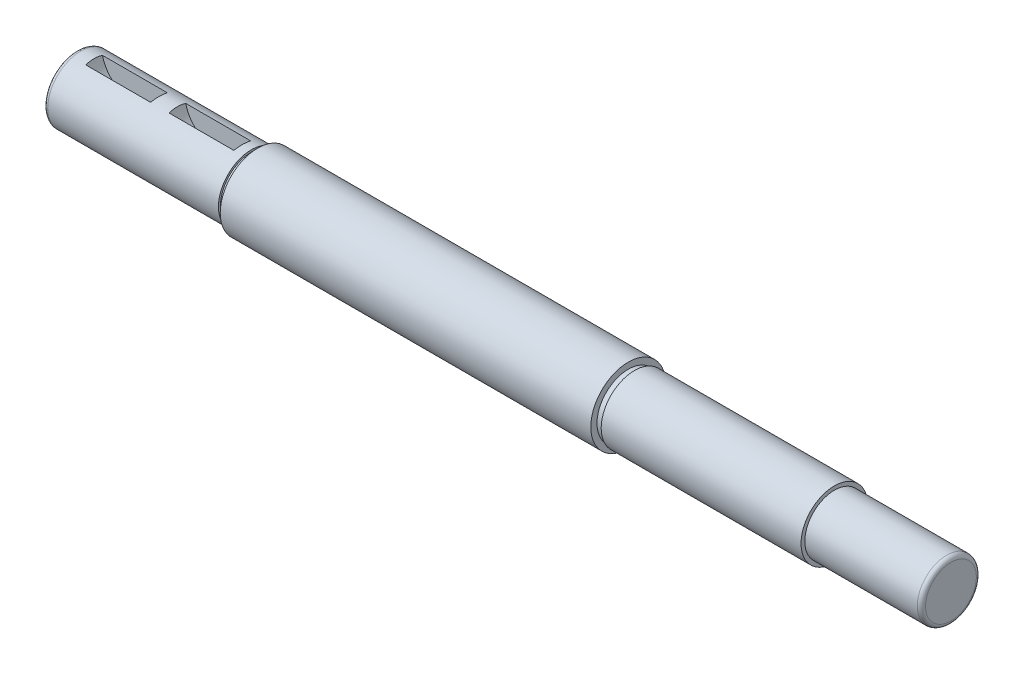
SolidWorks part; units mm, degrees
material "A-1"
ref_plane "Front Plane" through (0, 0, 0) normal (0, 0, 1) x (1, 0, 0)
ref_plane "Top Plane" through (0, 0, 0) normal (0, 1, 0) x (1, 0, 0)
ref_plane "Right Plane" through (0, 0, 0) normal (1, 0, 0) x (0, 0, -1)
sketch "Sketch1" plane through (0, 0, 0) normal (0, 0, 1) x (1, 0, 0)
  line L0 (-43.2189, 0) -> (45516.3918, 0) construction
  line L2 (-54.6287, 0) -> (-54.6287, 12.573)
  line L3 (-54.6287, 12.573) -> (12.0463, 12.573)
  line L4 (12.0463, 12.573) -> (12.0463, 11.7792)
  line L5 (12.0463, 11.7792) -> (14.4276, 11.7793)
  line L6 (14.4276, 11.7793) -> (14.4276, 14.2748)
  line L7 (14.4276, 14.2748) -> (155.7151, 14.2748)
  line L8 (155.7151, 14.2748) -> (155.7151, 11.9126)
  line L9 (155.7151, 11.9126) -> (158.0963, 11.9126)
  line L10 (158.0963, 11.9126) -> (158.0963, 12.7063)
  line L11 (158.0963, 12.7063) -> (234.2963, 12.7063)
  line L12 (234.2963, 12.7063) -> (234.2963, 11.2649)
  line L13 (234.2963, 11.2649) -> (278.7463, 11.2649)
  line L14 (278.7463, 11.2649) -> (278.7463, 0)
  line L15 (-54.6287, 0) -> (278.7463, 0)
  dimension "D1" = 25.146
  dimension "D2" = 66.675
  dimension "D3" = 0.7937
  dimension "D4" = 2.3813
  dimension "D5" = 28.5496
  dimension "D6" = 2.3813
  dimension "D7" = 0.7937
  dimension "D8" = 25.4127
  dimension "D9" = 22.5298
  dimension "D10" = 44.45
  dimension "D11" = 333.375
  dimension "D12" = 76.2
revolve "Revolve1" add sketch "Sketch1" angle 360 about L0
fillet "Fillet1" radius 1.5875 2 edges at (278.7463, 0, 11.2649) (-54.6287, 0, 12.573)
sketch "Sketch2" plane through (0, 0, 0) normal (0, 0, 1) x (1, 0, 0)
  line L0 (12.0463, 12.573) -> (-53.0412, 12.573) construction
  line L1 (-35.5787, 15.113) -> (-35.5787, 2.4403) construction
  line L2 (-54.6287, 10.9855) -> (-54.6287, -10.9855) construction
  line L3 (-48.0221, 12.573) -> (-23.1353, 12.573)
  arc A0 (-48.0221, 12.573) -> (-23.1353, 12.573) centre (-35.5787, 15.113) ccw
  point P8 (-35.5787, 2.413)
  dimension "D1" = 12.7
  dimension "D3" = 10.16
  dimension "D2" = 19.05
extrude "Cut-Extrude1" cut sketch "Sketch2" against normal mid plane 6.35 contours A0 L3
pattern_linear "LPattern1" count 2 spacing 31.75 along (1, 0, 0) of "Cut-Extrude1"
sketch "Sketch3" plane through (0, 0, 0) normal (0, 0, 1) x (1, 0, 0)
  line L1 (158.0963, -12.7063) -> (234.2963, -12.7063) construction
  line L2 (174.7651, -15.2463) -> (174.7651, -6.6993) construction
  line L3 (155.7151, -14.2748) -> (155.7151, 14.2748) construction
  line L4 (162.3217, -12.7064) -> (187.2085, -12.7064)
  line L5 (200.4217, -12.7064) -> (225.3085, -12.7064)
  arc A0 (162.3217, -12.7064) -> (187.2085, -12.7064) centre (174.7651, -15.2463) cw
  arc A1 (200.4217, -12.7064) -> (225.3085, -12.7064) centre (212.8651, -15.2463) cw
  point P8 (174.7651, -2.5463)
  dimension "D1" = 12.7
  dimension "D4" = 10.16
  dimension "D2" = 19.05
  dimension "D3" = 2
extrude "Cut-Extrude2" cut sketch "Sketch3" against normal mid plane 6.35
